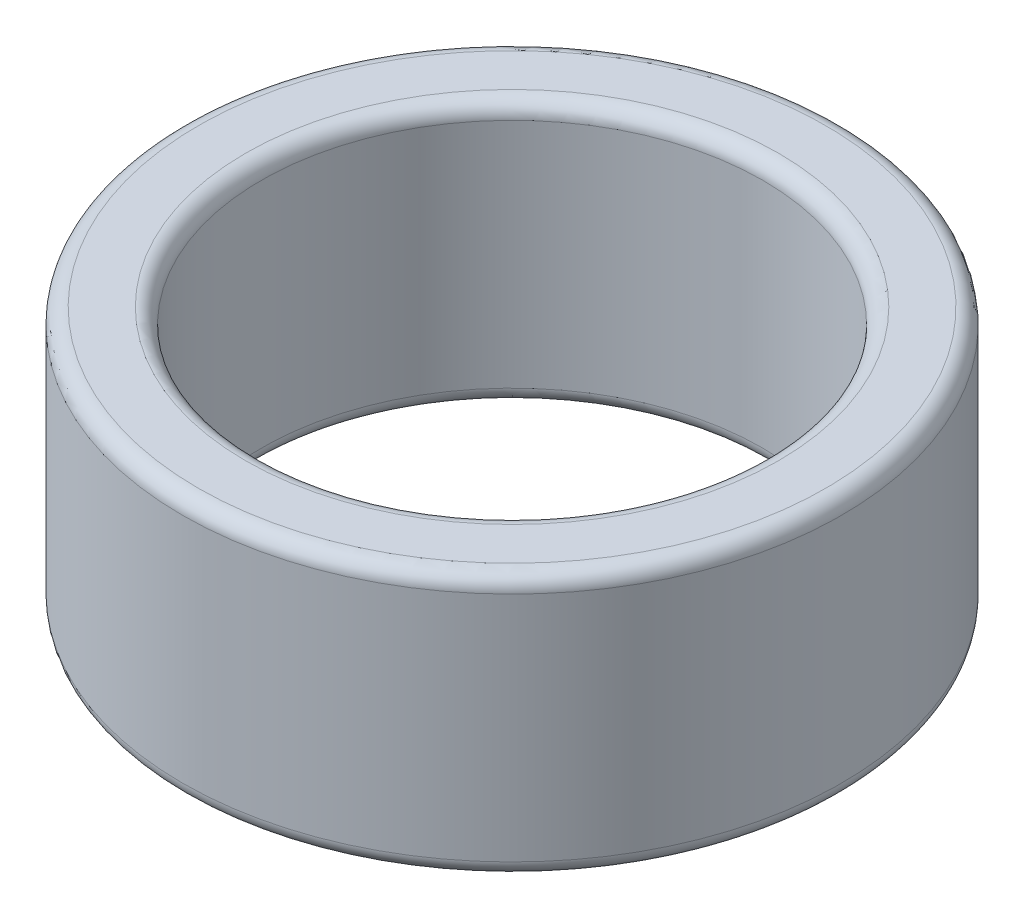
SolidWorks part; units mm, degrees
material "PE High Density"
ref_plane "Front" through (0, 0, 0) normal (0, 0, 1) x (1, 0, 0)
ref_plane "Top" through (0, 0, 0) normal (0, 1, 0) x (1, 0, 0)
ref_plane "Right" through (0, 0, 0) normal (1, 0, 0) x (0, 0, -1)
sketch "Sketch1" plane through (0, 0, 0) normal (0, 1, 0) x (1, 0, 0)
  circle A0 centre (0, 0) radius 5.2575
  circle A1 centre (0, 0) radius 4
  dimension "D1" = 10.515
  dimension "D2" = 8
extrude "Boss-Extrude1" add sketch "Sketch1" along normal blind 4.2
fillet "Fillet1" radius 0.25 4 edges at (0, 4.2, 5.2575) (0, 4.2, 4) (0, 0, 5.2575) (0, 0, 4)
